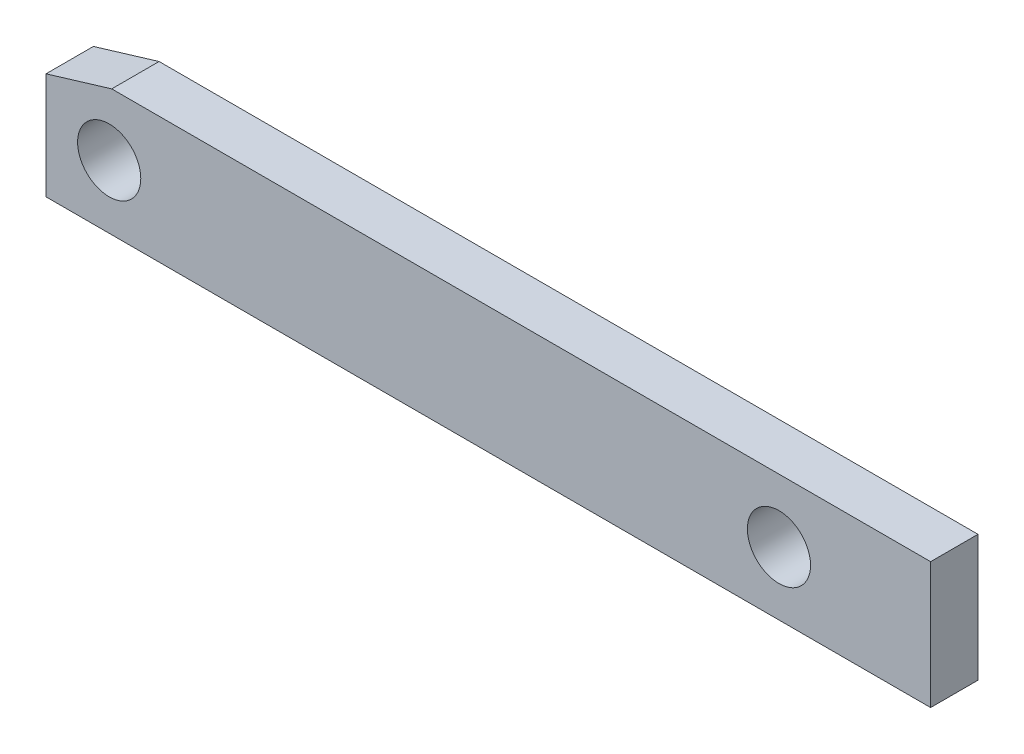
SolidWorks part; units mm, degrees
material "Plain Carbon Steel"
ref_plane "Front Plane" through (0, 0, 0) normal (0, 0, 1) x (1, 0, 0)
ref_plane "Top Plane" through (0, 0, 0) normal (0, 1, 0) x (1, 0, 0)
ref_plane "Right Plane" through (0, 0, 0) normal (1, 0, 0) x (0, 0, -1)
sketch "Sketch1" plane through (0, 0, 0) normal (0, 0, 1) x (1, 0, 0)
  line L1 (0, 0) -> (177.8, 0)
  line L2 (0, 0) -> (0, 25.4)
  line L3 (0, 25.4) -> (177.8, 25.4)
  line L4 (177.8, 0) -> (177.8, 25.4)
  dimension "D1" = 177.8
  dimension "D2" = 25.4
extrude "Boss-Extrude1" add sketch "Sketch1" along normal blind 9.525
hole_wizard "1/2 (0.5) Diameter Hole1" positions "Sketch2" profile "Sketch3" hole size "1/2" standard "ANSI Inch" end condition through all
sketch "Sketch2" plane through (0, 0, 9.525) normal (0, 0, 1) x (1, 0, 0)
  line L0 (177.8, 12.7) -> (0, 12.7) construction
  line L1 (177.8, 0) -> (177.8, 25.4) construction
  line L2 (0, 25.4) -> (0, 0) construction
  line L3 (88.9, 0) -> (88.9, 25.4) construction
  line L4 (0, 0) -> (177.8, 0) construction
  line L5 (177.8, 25.4) -> (0, 25.4) construction
  line L6 (0, 25.4) -> (0, 0) construction
  point P2 (12.7, 12.7)
  point P23 (147.32, 12.7)
  dimension "D1" = 12.7
  dimension "D2" = 134.62
sketch "Sketch3" plane through (12.7, 12.7, 9.525) normal (1, 0, 0) x (0, -1, 0)
  line L0 (0, 0) -> (0, 9.525)
  line L1 (0, 9.525) -> (6.35, 9.525)
  line L2 (6.35, 9.525) -> (6.35, 0)
  line L5 (6.35, 0) -> (0, 0)
  line L11 (0, -6.35) -> (0, 107.95) construction
  dimension "Thru Hole Dia." = 12.7
  dimension "Thru Hole Depth" = 9.525
sketch "Sketch5" plane through (0, 0, 9.525) normal (0, 0, 1) x (1, 0, 0)
  line L0 (20.8539, 28.7029) -> (28.7029, 4.5461) construction
  line L1 (20.8539, 28.7029) -> (-69.7342, -0.7309) construction
  line L2 (28.7029, 4.5461) -> (-61.8852, -24.8878) construction
  line L3 (-69.7342, -0.7309) -> (-61.8852, -24.8878) construction
  line L4 (13.208, 25.4) -> (0, 21.4191)
  line L5 (177.8, 25.4) -> (0, 25.4) construction
  line L6 (0, 25.4) -> (0, 0) construction
  line L7 (0, 21.4191) -> (0, 25.4)
  line L8 (0, 25.4) -> (13.208, 25.4)
  line L9 (0, 0) -> (177.8, 0) construction
  circle A1 centre (12.7, 12.7) radius 6.35 construction
  point P0 (12.7, 12.7)
  point P18 (0, 21.9271)
  dimension "D1" = 12.7
  dimension "D2" = 12.7
  dimension "D3" = 25.4
  dimension "D4" = 95.25
  dimension "D5" = 0.508
  dimension "D6" = 18
  dimension "D7" = 0.508
extrude "Cut-Extrude1" cut sketch "Sketch5" against normal through all
